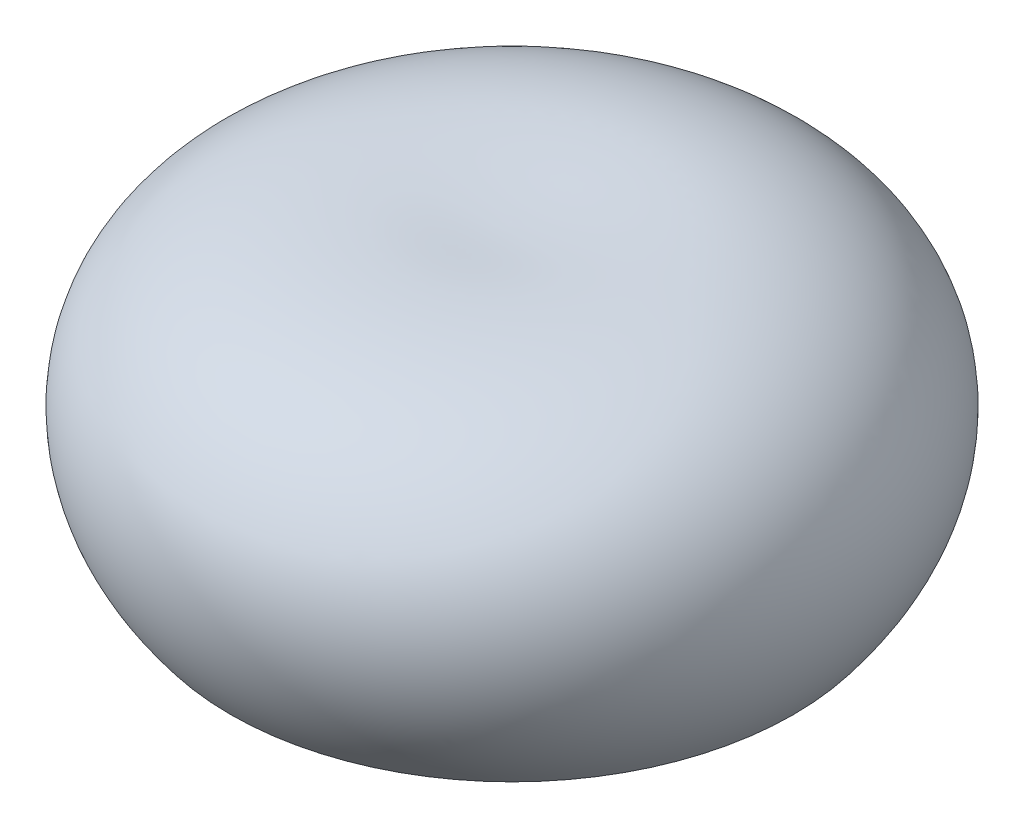
SolidWorks part; units mm, degrees
ref_plane "前视基准面" through (0, 0, 0) normal (0, 0, 1) x (1, 0, 0)
ref_plane "上视基准面" through (0, 0, 0) normal (0, 1, 0) x (1, 0, 0)
ref_plane "右视基准面" through (0, 0, 0) normal (1, 0, 0) x (0, 0, -1)
curve "曲线1"
  spline degree 3 poles (0, 7, 0) (0.0738, 6.9995, 0) (0.1783, 6.9989, 0) (0.3064, 7.0015, 0) (0.3805, 7.0034, 0) (0.4416, 7.0054, 0) (0.4951, 7.0074, 0) (0.5433, 7.0093, 0) (0.5877, 7.0113, 0) (0.629, 7.0132, 0) (0.6679, 7.0151, 0) (0.7047, 7.017, 0) (0.7397, 7.0189, 0) (0.7733, 7.0208, 0) (0.8056, 7.0227, 0) (0.8367, 7.0245, 0) (0.8668, 7.0264, 0) (0.8959, 7.0282, 0) (0.9242, 7.03, 0) (0.9518, 7.0318, 0) (0.9786, 7.0335, 0) (1.0048, 7.0353, 0) (1.0305, 7.037, 0) (1.0555, 7.0387, 0) (1.0801, 7.0405, 0) (1.1041, 7.0421, 0) (1.1278, 7.0438, 0) (1.151, 7.0455, 0) (1.1738, 7.0471, 0) (1.1962, 7.0487, 0) (1.2183, 7.0503, 0) (1.2401, 7.0519, 0) (1.2615, 7.0535, 0) (1.2826, 7.055, 0) (1.3035, 7.0566, 0) (1.3241, 7.0581, 0) (1.3444, 7.0596, 0) (1.3645, 7.0611, 0) (1.3843, 7.0626, 0) (1.4039, 7.064, 0) (1.4233, 7.0654, 0) (1.4425, 7.0669, 0) (1.4614, 7.0683, 0) (1.4802, 7.0697, 0) (1.4988, 7.071, 0) (1.5172, 7.0724, 0) (1.5355, 7.0737, 0) (1.5535, 7.0751, 0) (1.5714, 7.0764, 0) (1.5892, 7.0777, 0) (1.6068, 7.0789, 0) (1.6243, 7.0802, 0) (1.6416, 7.0815, 0) (1.6588, 7.0827, 0) (1.6758, 7.0839, 0) (1.6927, 7.0851, 0) (1.7095, 7.0863, 0) (1.7262, 7.0875, 0) (1.7427, 7.0886, 0) (1.7592, 7.0897, 0) (1.7755, 7.0909, 0) (1.7917, 7.092, 0) (1.8078, 7.0931, 0) (1.8238, 7.0941, 0) (1.8397, 7.0952, 0) (1.8555, 7.0962, 0) (1.8713, 7.0973, 0) (1.8869, 7.0983, 0) (1.9024, 7.0993, 0) (1.9178, 7.1003, 0) (1.9332, 7.1012, 0) (1.9485, 7.1022, 0) (1.9636, 7.1031, 0) (1.9788, 7.104, 0) (1.9938, 7.1049, 0) (2.0087, 7.1058, 0) (2.0236, 7.1067, 0) (2.0384, 7.1076, 0) (2.0531, 7.1084, 0) (2.0678, 7.1092, 0) (2.0823, 7.1101, 0) (2.0969, 7.1109, 0) (2.1113, 7.1116, 0) (2.1257, 7.1124, 0) (2.14, 7.1132, 0) (2.1543, 7.1139, 0) (2.1684, 7.1147, 0) (2.1826, 7.1154, 0) (2.1966, 7.1161, 0) (2.2107, 7.1167, 0) (2.2246, 7.1174, 0) (2.2385, 7.1181, 0) (2.2524, 7.1187, 0) (2.2661, 7.1193, 0) (2.2799, 7.1199, 0) (2.2936, 7.1205, 0) (2.3072, 7.1211, 0) (2.3208, 7.1217, 0) (2.3343, 7.1222, 0) (2.3478, 7.1228, 0) (2.3612, 7.1233, 0) (2.3746, 7.1238, 0) (2.3879, 7.1243, 0) (2.4012, 7.1248, 0) (2.4145, 7.1253, 0) (2.4277, 7.1257, 0) (2.4408, 7.1262, 0) (2.4539, 7.1266, 0) (2.467, 7.127, 0) (2.48, 7.1274, 0) (2.493, 7.1278, 0) (2.506, 7.1281, 0) (2.5189, 7.1285, 0) (2.5317, 7.1288, 0) (2.5446, 7.1292, 0) (2.5574, 7.1295, 0) (2.5701, 7.1298, 0) (2.5828, 7.1301, 0) (2.5955, 7.1303, 0) (2.6081, 7.1306, 0) (2.6207, 7.1308, 0) (2.6333, 7.1311, 0) (2.6458, 7.1313, 0) (2.6583, 7.1315, 0) (2.6708, 7.1317, 0) (2.6832, 7.1318, 0) (2.6956, 7.132, 0) (2.708, 7.1321, 0) (2.7203, 7.1323, 0) (2.7326, 7.1324, 0) (2.7449, 7.1325, 0) (2.7571, 7.1326, 0) (2.7693, 7.1327, 0) (2.7815, 7.1327, 0) (2.7937, 7.1328, 0) (2.8058, 7.1328, 0) (2.8179, 7.1328, 0) (2.8299, 7.1329, 0) (2.8419, 7.1328, 0) (2.8539, 7.1328, 0) (2.8659, 7.1328, 0) (2.8779, 7.1328, 0) (2.8898, 7.1327, 0) (2.9017, 7.1326, 0) (2.9135, 7.1325, 0) (2.9254, 7.1324, 0) (2.9372, 7.1323, 0) (2.949, 7.1322, 0) (2.9607, 7.1321, 0) (2.9725, 7.1319, 0) (2.9842, 7.1317, 0) (2.9958, 7.1316, 0) (3.0075, 7.1314, 0) (3.0191, 7.1312, 0) (3.0307, 7.1309, 0) (3.0423, 7.1307, 0) (3.0539, 7.1305, 0) (3.0654, 7.1302, 0) (3.0769, 7.1299, 0) (3.0884, 7.1296, 0) (3.0999, 7.1293, 0) (3.1114, 7.129, 0) (3.1228, 7.1287, 0) (3.1342, 7.1284, 0) (3.1456, 7.128, 0) (3.1569, 7.1277, 0) (3.1683, 7.1273, 0) (3.1796, 7.1269, 0) (3.1909, 7.1265, 0) (3.2021, 7.1261, 0) (3.2134, 7.1256, 0) (3.2246, 7.1252, 0) (3.2358, 7.1247, 0) (3.247, 7.1243, 0) (3.2582, 7.1238, 0) (3.2694, 7.1233, 0) (3.2805, 7.1228, 0) (3.2916, 7.1222, 0) (3.3027, 7.1217, 0) (3.3138, 7.1211, 0) (3.3248, 7.1206, 0) (3.3359, 7.12, 0) (3.3469, 7.1194, 0) (3.3579, 7.1188, 0) (3.3689, 7.1182, 0) (3.3798, 7.1176, 0) (3.3908, 7.1169, 0) (3.4017, 7.1163, 0) (3.4126, 7.1156, 0) (3.4235, 7.1149, 0) (3.4344, 7.1142, 0) (3.4452, 7.1135, 0) (3.4561, 7.1128, 0) (3.4669, 7.1121, 0) (3.4777, 7.1113, 0) (3.4885, 7.1106, 0) (3.4993, 7.1098, 0) (3.51, 7.109, 0) (3.5208, 7.1082, 0) (3.5315, 7.1074, 0) (3.5422, 7.1066, 0) (3.5529, 7.1058, 0) (3.5635, 7.1049, 0) (3.5742, 7.104, 0) (3.5848, 7.1032, 0) (3.5955, 7.1023, 0) (3.6061, 7.1014, 0) (3.6167, 7.1005, 0) (3.6273, 7.0995, 0) (3.6378, 7.0986, 0) (3.6484, 7.0977, 0) (3.6589, 7.0967, 0) (3.6694, 7.0957, 0) (3.6799, 7.0947, 0) (3.6904, 7.0937, 0) (3.7009, 7.0927, 0) (3.7114, 7.0917, 0) (3.7218, 7.0906, 0) (3.7322, 7.0896, 0) (3.7426, 7.0885, 0) (3.753, 7.0874, 0) (3.7634, 7.0863, 0) (3.7738, 7.0852, 0) (3.7842, 7.0841, 0) (3.7945, 7.083, 0) (3.8049, 7.0818, 0) (3.8152, 7.0807, 0) (3.8255, 7.0795, 0) (3.8358, 7.0783, 0) (3.846, 7.0771, 0) (3.8563, 7.0759, 0) (3.8666, 7.0747, 0) (3.8768, 7.0734, 0) (3.887, 7.0722, 0) (3.8972, 7.0709, 0) (3.9074, 7.0697, 0) (3.9176, 7.0684, 0) (3.9278, 7.0671, 0) (3.938, 7.0658, 0) (3.9481, 7.0644, 0) (3.9582, 7.0631, 0) (3.9684, 7.0618, 0) (3.9785, 7.0604, 0) (3.9886, 7.059, 0) (3.9986, 7.0576, 0) (4.0087, 7.0562, 0) (4.0188, 7.0548, 0) (4.0288, 7.0534, 0) (4.0389, 7.0519, 0) (4.0489, 7.0505, 0) (4.0589, 7.049, 0) (4.0689, 7.0475, 0) (4.0789, 7.0461, 0) (4.0889, 7.0445, 0) (4.0988, 7.043, 0) (4.1088, 7.0415, 0) (4.1187, 7.04, 0) (4.1286, 7.0384, 0) (4.1386, 7.0368, 0) (4.1485, 7.0352, 0) (4.1584, 7.0337, 0) (4.1682, 7.032, 0) (4.1781, 7.0304, 0) (4.188, 7.0288, 0) (4.1978, 7.0271, 0) (4.2076, 7.0255, 0) (4.2175, 7.0238, 0) (4.2273, 7.0221, 0) (4.2371, 7.0204, 0) (4.2469, 7.0187, 0) (4.2567, 7.017, 0) (4.2664, 7.0153, 0) (4.2762, 7.0135, 0) (4.2859, 7.0118, 0) (4.2957, 7.01, 0) (4.3054, 7.0082, 0) (4.3151, 7.0064, 0) (4.3248, 7.0046, 0) (4.3345, 7.0028, 0) (4.3442, 7.0009, 0) (4.3539, 6.9991, 0) (4.3635, 6.9972, 0) (4.3732, 6.9953, 0) (4.3828, 6.9934, 0) (4.3924, 6.9915, 0) (4.4021, 6.9896, 0) (4.4117, 6.9877, 0) (4.4213, 6.9858, 0) (4.4309, 6.9838, 0) (4.4404, 6.9818, 0) (4.45, 6.9799, 0) (4.4596, 6.9779, 0) (4.4691, 6.9759, 0) (4.4786, 6.9738, 0) (4.4882, 6.9718, 0) (4.4977, 6.9698, 0) (4.5072, 6.9677, 0) (4.5167, 6.9656, 0) (4.5262, 6.9635, 0) (4.5356, 6.9615, 0) (4.5451, 6.9593, 0) (4.5546, 6.9572, 0) (4.564, 6.9551, 0) (4.5734, 6.9529, 0) (4.5829, 6.9508, 0) (4.5923, 6.9486, 0) (4.6017, 6.9464, 0) (4.6111, 6.9442, 0) (4.6205, 6.942, 0) (4.6299, 6.9398, 0) (4.6392, 6.9375, 0) (4.6486, 6.9353, 0) (4.6579, 6.933, 0) (4.6673, 6.9307, 0) (4.6766, 6.9284, 0) (4.6859, 6.9261, 0) (4.6952, 6.9238, 0) (4.7045, 6.9215, 0) (4.7138, 6.9192, 0) (4.7231, 6.9168, 0) (4.7324, 6.9144, 0) (4.7416, 6.912, 0) (4.7509, 6.9096, 0) (4.7601, 6.9072, 0) (4.7693, 6.9048, 0) (4.7786, 6.9024, 0) (4.7878, 6.8999, 0) (4.797, 6.8975, 0) (4.8062, 6.895, 0) (4.8154, 6.8925, 0) (4.8245, 6.89, 0) (4.8337, 6.8875, 0) (4.8429, 6.885, 0) (4.852, 6.8824, 0) (4.8612, 6.8799, 0) (4.8703, 6.8773, 0) (4.8794, 6.8747, 0) (4.8885, 6.8721, 0) (4.8976, 6.8695, 0) (4.9067, 6.8669, 0) (4.9158, 6.8643, 0) (4.9249, 6.8616, 0) (4.9339, 6.859, 0) (4.943, 6.8563, 0) (4.952, 6.8536, 0) (4.9611, 6.8509, 0) (4.9701, 6.8482, 0) (4.9791, 6.8455, 0) (4.9881, 6.8428, 0) (4.9971, 6.84, 0) (5.0061, 6.8372, 0) (5.0151, 6.8345, 0) (5.0241, 6.8317, 0) (5.0331, 6.8289, 0) (5.042, 6.8261, 0) (5.051, 6.8232, 0) (5.0599, 6.8204, 0) (5.0688, 6.8175, 0) (5.0778, 6.8147, 0) (5.0867, 6.8118, 0) (5.0956, 6.8089, 0) (5.1045, 6.806, 0) (5.1134, 6.803, 0) (5.1222, 6.8001, 0) (5.1311, 6.7971, 0) (5.14, 6.7942, 0) (5.1488, 6.7912, 0) (5.1576, 6.7882, 0) (5.1665, 6.7852, 0) (5.1753, 6.7822, 0) (5.1841, 6.7792, 0) (5.1929, 6.7761, 0) (5.2017, 6.7731, 0) (5.2105, 6.77, 0) (5.2193, 6.7669, 0) (5.228, 6.7638, 0) (5.2368, 6.7607, 0) (5.2456, 6.7576, 0) (5.2543, 6.7544, 0) (5.263, 6.7513, 0) (5.2718, 6.7481, 0) (5.2805, 6.7449, 0) (5.2892, 6.7417, 0) (5.2979, 6.7385, 0) (5.3066, 6.7353, 0) (5.3153, 6.7321, 0) (5.3239, 6.7288, 0) (5.3326, 6.7256, 0) (5.3412, 6.7223, 0) (5.3499, 6.719, 0) (5.3585, 6.7157, 0) (5.3671, 6.7124, 0) (5.3758, 6.709, 0) (5.3844, 6.7057, 0) (5.393, 6.7023, 0) (5.4016, 6.699, 0) (5.4102, 6.6956, 0) (5.4187, 6.6922, 0) (5.4273, 6.6888, 0) (5.4359, 6.6854, 0) (5.4444, 6.6819, 0) (5.4529, 6.6785, 0) (5.4615, 6.675, 0) (5.47, 6.6715, 0) (5.4785, 6.668, 0) (5.487, 6.6645, 0) (5.4955, 6.661, 0) (5.504, 6.6575, 0) (5.5125, 6.6539, 0) (5.5209, 6.6503, 0) (5.5294, 6.6468, 0) (5.5378, 6.6432, 0) (5.5463, 6.6396, 0) (5.5547, 6.6359, 0) (5.5631, 6.6323, 0) (5.5716, 6.6287, 0) (5.58, 6.625, 0) (5.5884, 6.6213, 0) (5.5968, 6.6176, 0) (5.6051, 6.6139, 0) (5.6135, 6.6102, 0) (5.6219, 6.6065, 0) (5.6302, 6.6027, 0) (5.6386, 6.599, 0) (5.6469, 6.5952, 0) (5.6552, 6.5914, 0) (5.6635, 6.5876, 0) (5.6719, 6.5838, 0) (5.6802, 6.58, 0) (5.6884, 6.5761, 0) (5.6967, 6.5723, 0) (5.705, 6.5684, 0) (5.7133, 6.5645, 0) (5.7215, 6.5606, 0) (5.7298, 6.5567, 0) (5.738, 6.5528, 0) (5.7462, 6.5488, 0) (5.7544, 6.5449, 0) (5.7627, 6.5409, 0) (5.7709, 6.5369, 0) (5.7791, 6.5329, 0) (5.7872, 6.5289, 0) (5.7954, 6.5249, 0) (5.8036, 6.5208, 0) (5.8117, 6.5168, 0) (5.8199, 6.5127, 0) (5.828, 6.5086, 0) (5.8361, 6.5045, 0) (5.8443, 6.5004, 0) (5.8524, 6.4962, 0) (5.8605, 6.4921, 0) (5.8686, 6.4879, 0) (5.8766, 6.4838, 0) (5.8847, 6.4796, 0) (5.8928, 6.4754, 0) (5.9008, 6.4712, 0) (5.9089, 6.4669, 0) (5.9169, 6.4627, 0) (5.9249, 6.4584, 0) (5.933, 6.4541, 0) (5.941, 6.4499, 0) (5.949, 6.4456, 0) (5.957, 6.4412, 0) (5.9649, 6.4369, 0) (5.9729, 6.4326, 0) (5.9809, 6.4282, 0) (5.9888, 6.4238, 0) (5.9968, 6.4194, 0) (6.0047, 6.415, 0) (6.0126, 6.4106, 0) (6.0206, 6.4062, 0) (6.0285, 6.4017, 0) (6.0364, 6.3972, 0) (6.0442, 6.3928, 0) (6.0521, 6.3883, 0) (6.06, 6.3838, 0) (6.0679, 6.3792, 0) (6.0757, 6.3747, 0) (6.0835, 6.3701, 0) (6.0914, 6.3656, 0) (6.0992, 6.361, 0) (6.107, 6.3564, 0) (6.1148, 6.3518, 0) (6.1226, 6.3471, 0) (6.1304, 6.3425, 0) (6.1382, 6.3378, 0) (6.1459, 6.3332, 0) (6.1537, 6.3285, 0) (6.1614, 6.3238, 0) (6.1692, 6.319, 0) (6.1769, 6.3143, 0) (6.1846, 6.3096, 0) (6.1923, 6.3048, 0) (6.2, 6.3, 0) (6.2077, 6.2952, 0) (6.2154, 6.2904, 0) (6.223, 6.2856, 0) (6.2307, 6.2807, 0) (6.2383, 6.2759, 0) (6.246, 6.271, 0) (6.2536, 6.2661, 0) (6.2612, 6.2612, 0) (6.2688, 6.2563, 0) (6.2764, 6.2514, 0) (6.284, 6.2464, 0) (6.2916, 6.2415, 0) (6.2991, 6.2365, 0) (6.3067, 6.2315, 0) (6.3143, 6.2265, 0) (6.3218, 6.2214, 0) (6.3293, 6.2164, 0) (6.3368, 6.2113, 0) (6.3443, 6.2063, 0) (6.3518, 6.2012, 0) (6.3593, 6.1961, 0) (6.3668, 6.191, 0) (6.3743, 6.1858, 0) (6.3817, 6.1807, 0) (6.3892, 6.1755, 0) (6.3966, 6.1703, 0) (6.404, 6.1651, 0) (6.4114, 6.1599, 0) (6.4189, 6.1547, 0) (6.4262, 6.1494, 0) (6.4336, 6.1442, 0) (6.441, 6.1389, 0) (6.4484, 6.1336, 0) (6.4557, 6.1283, 0) (6.4631, 6.123, 0) (6.4704, 6.1177, 0) (6.4777, 6.1123, 0) (6.485, 6.1069, 0) (6.4923, 6.1015, 0) (6.4996, 6.0961, 0) (6.5069, 6.0907, 0) (6.5142, 6.0853, 0) (6.5214, 6.0798, 0) (6.5287, 6.0744, 0) (6.5359, 6.0689, 0) (6.5431, 6.0634, 0) (6.5503, 6.0579, 0) (6.5575, 6.0523, 0) (6.5647, 6.0468, 0) (6.5719, 6.0412, 0) (6.5791, 6.0356, 0) (6.5862, 6.0301, 0) (6.5934, 6.0244, 0) (6.6005, 6.0188, 0) (6.6077, 6.0132, 0) (6.6148, 6.0075, 0) (6.6219, 6.0018, 0) (6.629, 5.9961, 0) (6.6361, 5.9904, 0) (6.6431, 5.9847, 0) (6.6502, 5.979, 0) (6.6572, 5.9732, 0) (6.6643, 5.9674, 0) (6.6713, 5.9616, 0) (6.6783, 5.9558, 0) (6.6853, 5.95, 0) (6.6923, 5.9441, 0) (6.6993, 5.9383, 0) (6.7063, 5.9324, 0) (6.7132, 5.9265, 0) (6.7202, 5.9206, 0) (6.7271, 5.9147, 0) (6.734, 5.9087, 0) (6.7409, 5.9028, 0) (6.7478, 5.8968, 0) (6.7547, 5.8908, 0) (6.7616, 5.8848, 0) (6.7685, 5.8788, 0) (6.7753, 5.8727, 0) (6.7822, 5.8667, 0) (6.789, 5.8606, 0) (6.7958, 5.8545, 0) (6.8026, 5.8484, 0) (6.8094, 5.8423, 0) (6.8162, 5.8361, 0) (6.823, 5.83, 0) (6.8297, 5.8238, 0) (6.8365, 5.8176, 0) (6.8432, 5.8114, 0) (6.8499, 5.8051, 0) (6.8566, 5.7989, 0) (6.8633, 5.7926, 0) (6.87, 5.7863, 0) (6.8767, 5.78, 0) (6.8834, 5.7737, 0) (6.89, 5.7674, 0) (6.8966, 5.761, 0) (6.9033, 5.7547, 0) (6.9099, 5.7483, 0) (6.9165, 5.7419, 0) (6.9231, 5.7355, 0) (6.9296, 5.729, 0) (6.9362, 5.7226, 0) (6.9428, 5.7161, 0) (6.9493, 5.7096, 0) (6.9558, 5.7031, 0) (6.9623, 5.6966, 0) (6.9688, 5.69, 0) (6.9753, 5.6835, 0) (6.9818, 5.6769, 0) (6.9882, 5.6703, 0) (6.9947, 5.6637, 0) (7.0011, 5.657, 0) (7.0075, 5.6504, 0) (7.014, 5.6437, 0) (7.0204, 5.637, 0) (7.0267, 5.6303, 0) (7.0331, 5.6236, 0) (7.0395, 5.6169, 0) (7.0458, 5.6101, 0) (7.0521, 5.6033, 0) (7.0584, 5.5965, 0) (7.0647, 5.5897, 0) (7.071, 5.5829, 0) (7.0773, 5.576, 0) (7.0836, 5.5692, 0) (7.0898, 5.5623, 0) (7.0961, 5.5554, 0) (7.1023, 5.5484, 0) (7.1085, 5.5415, 0) (7.1147, 5.5345, 0) (7.1209, 5.5276, 0) (7.127, 5.5206, 0) (7.1332, 5.5135, 0) (7.1393, 5.5065, 0) (7.1454, 5.4995, 0) (7.1515, 5.4924, 0) (7.1576, 5.4853, 0) (7.1637, 5.4782, 0) (7.1698, 5.4711, 0) (7.1758, 5.4639, 0) (7.1819, 5.4567, 0) (7.1879, 5.4496, 0) (7.1939, 5.4424, 0) (7.1999, 5.4351, 0) (7.2059, 5.4279, 0) (7.2119, 5.4206, 0) (7.2178, 5.4134, 0) (7.2238, 5.4061, 0) (7.2297, 5.3987, 0) (7.2356, 5.3914, 0) (7.2415, 5.3841, 0) (7.2474, 5.3767, 0) (7.2532, 5.3693, 0) (7.2591, 5.3619, 0) (7.2649, 5.3544, 0) (7.2707, 5.347, 0) (7.2765, 5.3395, 0) (7.2823, 5.332, 0) (7.2881, 5.3245, 0) (7.2939, 5.317, 0) (7.2996, 5.3094, 0) (7.3053, 5.3019, 0) (7.311, 5.2943, 0) (7.3167, 5.2867, 0) (7.3224, 5.279, 0) (7.3281, 5.2714, 0) (7.3337, 5.2637, 0) (7.3394, 5.256, 0) (7.345, 5.2483, 0) (7.3506, 5.2406, 0) (7.3562, 5.2329, 0) (7.3618, 5.2251, 0) (7.3673, 5.2173, 0) (7.3729, 5.2095, 0) (7.3784, 5.2017, 0) (7.3839, 5.1938, 0) (7.3894, 5.1859, 0) (7.3949, 5.1781, 0) (7.4003, 5.1702, 0) (7.4058, 5.1622, 0) (7.4112, 5.1543, 0) (7.4166, 5.1463, 0) (7.422, 5.1383, 0) (7.4274, 5.1303, 0) (7.4327, 5.1223, 0) (7.4381, 5.1142, 0) (7.4434, 5.1061, 0) (7.4487, 5.098, 0) (7.454, 5.0899, 0) (7.4593, 5.0818, 0) (7.4646, 5.0736, 0) (7.4698, 5.0655, 0) (7.475, 5.0573, 0) (7.4802, 5.049, 0) (7.4854, 5.0408, 0) (7.4906, 5.0325, 0) (7.4958, 5.0243, 0) (7.5009, 5.016, 0) (7.506, 5.0076, 0) (7.5111, 4.9993, 0) (7.5162, 4.9909, 0) (7.5213, 4.9825, 0) (7.5263, 4.9741, 0) (7.5314, 4.9657, 0) (7.5364, 4.9572, 0) (7.5414, 4.9487, 0) (7.5464, 4.9402, 0) (7.5513, 4.9317, 0) (7.5563, 4.9232, 0) (7.5612, 4.9146, 0) (7.5661, 4.906, 0) (7.571, 4.8974, 0) (7.5758, 4.8888, 0) (7.5807, 4.8801, 0) (7.5855, 4.8715, 0) (7.5903, 4.8628, 0) (7.5951, 4.8541, 0) (7.5999, 4.8453, 0) (7.6047, 4.8366, 0) (7.6094, 4.8278, 0) (7.6141, 4.819, 0) (7.6188, 4.8101, 0) (7.6235, 4.8013, 0) (7.6282, 4.7924, 0) (7.6328, 4.7835, 0) (7.6374, 4.7746, 0) (7.642, 4.7656, 0) (7.6466, 4.7567, 0) (7.6512, 4.7477, 0) (7.6557, 4.7387, 0) (7.6602, 4.7296, 0) (7.6647, 4.7206, 0) (7.6692, 4.7115, 0) (7.6737, 4.7024, 0) (7.6781, 4.6932, 0) (7.6825, 4.6841, 0) (7.6869, 4.6749, 0) (7.6913, 4.6657, 0) (7.6957, 4.6565, 0) (7.7, 4.6472, 0) (7.7043, 4.638, 0) (7.7086, 4.6287, 0) (7.7129, 4.6193, 0) (7.7172, 4.61, 0) (7.7214, 4.6006, 0) (7.7256, 4.5912, 0) (7.7298, 4.5818, 0) (7.734, 4.5724, 0) (7.7381, 4.5629, 0) (7.7422, 4.5534, 0) (7.7463, 4.5439, 0) (7.7504, 4.5344, 0) (7.7545, 4.5248, 0) (7.7585, 4.5152, 0) (7.7625, 4.5056, 0) (7.7665, 4.496, 0) (7.7705, 4.4863, 0) (7.7744, 4.4766, 0) (7.7784, 4.4669, 0) (7.7823, 4.4571, 0) (7.7861, 4.4474, 0) (7.79, 4.4376, 0) (7.7938, 4.4278, 0) (7.7976, 4.4179, 0) (7.8014, 4.4081, 0) (7.8052, 4.3982, 0) (7.8089, 4.3882, 0) (7.8127, 4.3783, 0) (7.8164, 4.3683, 0) (7.82, 4.3583, 0) (7.8237, 4.3483, 0) (7.8273, 4.3382, 0) (7.8309, 4.3282, 0) (7.8345, 4.3181, 0) (7.838, 4.3079, 0) (7.8415, 4.2978, 0) (7.845, 4.2876, 0) (7.8485, 4.2774, 0) (7.852, 4.2671, 0) (7.8554, 4.2569, 0) (7.8588, 4.2466, 0) (7.8622, 4.2362, 0) (7.8655, 4.2259, 0) (7.8688, 4.2155, 0) (7.8721, 4.2051, 0) (7.8754, 4.1947, 0) (7.8786, 4.1842, 0) (7.8819, 4.1737, 0) (7.8851, 4.1632, 0) (7.8882, 4.1527, 0) (7.8914, 4.1421, 0) (7.8945, 4.1315, 0) (7.8976, 4.1209, 0) (7.9006, 4.1102, 0) (7.9037, 4.0995, 0) (7.9067, 4.0888, 0) (7.9096, 4.078, 0) (7.9126, 4.0673, 0) (7.9155, 4.0565, 0) (7.9184, 4.0456, 0) (7.9213, 4.0348, 0) (7.9241, 4.0239, 0) (7.9269, 4.0129, 0) (7.9297, 4.002, 0) (7.9325, 3.991, 0) (7.9352, 3.98, 0) (7.9379, 3.9689, 0) (7.9406, 3.9579, 0) (7.9432, 3.9468, 0) (7.9458, 3.9356, 0) (7.9484, 3.9244, 0) (7.951, 3.9132, 0) (7.9535, 3.902, 0) (7.956, 3.8908, 0) (7.9584, 3.8795, 0) (7.9609, 3.8681, 0) (7.9633, 3.8568, 0) (7.9656, 3.8454, 0) (7.968, 3.834, 0) (7.9703, 3.8225, 0) (7.9725, 3.811, 0) (7.9748, 3.7995, 0) (7.977, 3.7879, 0) (7.9792, 3.7763, 0) (7.9813, 3.7647, 0) (7.9834, 3.7531, 0) (7.9855, 3.7414, 0) (7.9876, 3.7297, 0) (7.9896, 3.7179, 0) (7.9916, 3.7061, 0) (7.9935, 3.6943, 0) (7.9955, 3.6824, 0) (7.9973, 3.6705, 0) (7.9992, 3.6586, 0) (8.001, 3.6466, 0) (8.0028, 3.6346, 0) (8.0045, 3.6226, 0) (8.0062, 3.6105, 0) (8.0079, 3.5984, 0) (8.0096, 3.5863, 0) (8.0112, 3.5741, 0) (8.0127, 3.5619, 0) (8.0143, 3.5496, 0) (8.0158, 3.5373, 0) (8.0172, 3.525, 0) (8.0187, 3.5126, 0) (8.0201, 3.5002, 0) (8.0214, 3.4878, 0) (8.0227, 3.4753, 0) (8.024, 3.4628, 0) (8.0252, 3.4502, 0) (8.0264, 3.4376, 0) (8.0276, 3.425, 0) (8.0287, 3.4123, 0) (8.0298, 3.3996, 0) (8.0308, 3.3868, 0) (8.0318, 3.374, 0) (8.0328, 3.3612, 0) (8.0337, 3.3483, 0) (8.0346, 3.3354, 0) (8.0354, 3.3224, 0) (8.0362, 3.3094, 0) (8.037, 3.2964, 0) (8.0377, 3.2833, 0) (8.0384, 3.2701, 0) (8.039, 3.257, 0) (8.0396, 3.2437, 0) (8.0401, 3.2305, 0) (8.0406, 3.2172, 0) (8.0411, 3.2038, 0) (8.0415, 3.1904, 0) (8.0419, 3.177, 0) (8.0422, 3.1635, 0) (8.0425, 3.1499, 0) (8.0427, 3.1364, 0) (8.0429, 3.1227, 0) (8.043, 3.109, 0) (8.0431, 3.0953, 0) (8.0431, 3.0815, 0) (8.0431, 3.0677, 0) (8.0431, 3.0539, 0) (8.043, 3.0399, 0) (8.0428, 3.026, 0) (8.0426, 3.0119, 0) (8.0423, 2.9979, 0) (8.042, 2.9837, 0) (8.0417, 2.9696, 0) (8.0413, 2.9553, 0) (8.0408, 2.9411, 0) (8.0403, 2.9267, 0) (8.0397, 2.9123, 0) (8.0391, 2.8979, 0) (8.0384, 2.8834, 0) (8.0377, 2.8688, 0) (8.0369, 2.8542, 0) (8.0361, 2.8396, 0) (8.0352, 2.8248, 0) (8.0342, 2.8101, 0) (8.0332, 2.7952, 0) (8.0321, 2.7803, 0) (8.031, 2.7653, 0) (8.0298, 2.7503, 0) (8.0286, 2.7352, 0) (8.0272, 2.7201, 0) (8.0259, 2.7049, 0) (8.0244, 2.6896, 0) (8.0229, 2.6743, 0) (8.0214, 2.6589, 0) (8.0197, 2.6434, 0) (8.018, 2.6279, 0) (8.0163, 2.6123, 0) (8.0144, 2.5966, 0) (8.0125, 2.5809, 0) (8.0106, 2.5651, 0) (8.0085, 2.5492, 0) (8.0064, 2.5332, 0) (8.0042, 2.5172, 0) (8.002, 2.5011, 0) (7.9997, 2.4849, 0) (7.9973, 2.4687, 0) (7.9948, 2.4523, 0) (7.9922, 2.4359, 0) (7.9896, 2.4194, 0) (7.9869, 2.4028, 0) (7.9841, 2.3862, 0) (7.9812, 2.3694, 0) (7.9783, 2.3526, 0) (7.9752, 2.3357, 0) (7.9721, 2.3187, 0) (7.9689, 2.3016, 0) (7.9656, 2.2844, 0) (7.9622, 2.2672, 0) (7.9587, 2.2498, 0) (7.9552, 2.2324, 0) (7.9515, 2.2148, 0) (7.9477, 2.1971, 0) (7.9439, 2.1794, 0) (7.9399, 2.1615, 0) (7.9359, 2.1435, 0) (7.9317, 2.1255, 0) (7.9274, 2.1073, 0) (7.9231, 2.089, 0) (7.9186, 2.0706, 0) (7.914, 2.052, 0) (7.9093, 2.0334, 0) (7.9045, 2.0146, 0) (7.8995, 1.9957, 0) (7.8945, 1.9767, 0) (7.8893, 1.9576, 0) (7.884, 1.9383, 0) (7.8786, 1.9189, 0) (7.873, 1.8993, 0) (7.8673, 1.8796, 0) (7.8615, 1.8597, 0) (7.8555, 1.8397, 0) (7.8494, 1.8196, 0) (7.8431, 1.7993, 0) (7.8367, 1.7788, 0) (7.8301, 1.7581, 0) (7.8234, 1.7373, 0) (7.8165, 1.7163, 0) (7.8094, 1.6951, 0) (7.8022, 1.6738, 0) (7.7948, 1.6522, 0) (7.7872, 1.6304, 0) (7.7794, 1.6084, 0) (7.7714, 1.5862, 0) (7.7632, 1.5638, 0) (7.7548, 1.5411, 0) (7.7461, 1.5182, 0) (7.7373, 1.4951, 0) (7.7282, 1.4717, 0) (7.7188, 1.448, 0) (7.7093, 1.424, 0) (7.6994, 1.3998, 0) (7.6893, 1.3752, 0) (7.6789, 1.3503, 0) (7.6681, 1.3251, 0) (7.6571, 1.2995, 0) (7.6457, 1.2735, 0) (7.634, 1.2471, 0) (7.6219, 1.2203, 0) (7.6095, 1.1931, 0) (7.5966, 1.1654, 0) (7.5833, 1.1372, 0) (7.5695, 1.1084, 0) (7.5552, 1.0791, 0) (7.5404, 1.0491, 0) (7.525, 1.0185, 0) (7.5091, 0.9872, 0) (7.4924, 0.9551, 0) (7.475, 0.9221, 0) (7.4568, 0.8881, 0) (7.4377, 0.8532, 0) (7.4177, 0.817, 0) (7.3965, 0.7795, 0) (7.374, 0.7405, 0) (7.3502, 0.6997, 0) (7.3246, 0.6569, 0) (7.297, 0.6116, 0) (7.2669, 0.5632, 0) (7.2337, 0.511, 0) (7.1963, 0.4536, 0) (7.1528, 0.3886, 0) (7.0992, 0.3106, 0) (7.0057, 0.179, 0) (6.9269, 0.0739, 0) (6.8715, 0, 0) knots 0 0 0 0 0.016298 0.023067 0.028274 0.032675 0.036563 0.040086 0.043333 0.046364 0.049217 0.051922 0.054501 0.056971 0.059346 0.061636 0.063851 0.065998 0.068084 0.070114 0.072093 0.074025 0.075913 0.077761 0.079571 0.081346 0.083088 0.0848 0.086482 0.088137 0.089766 0.091371 0.092952 0.094511 0.096049 0.097567 0.099066 0.100547 0.10201 0.103456 0.104887 0.106302 0.107702 0.109087 0.110459 0.111818 0.113164 0.114497 0.115819 0.117129 0.118427 0.119715 0.120993 0.12226 0.123518 0.124766 0.126004 0.127234 0.128455 0.129667 0.130871 0.132067 0.133256 0.134436 0.135609 0.136775 0.137933 0.139085 0.14023 0.141368 0.1425 0.143626 0.144745 0.145859 0.146966 0.148068 0.149164 0.150255 0.15134 0.15242 0.153495 0.154564 0.155629 0.156689 0.157744 0.158794 0.159839 0.160881 0.161917 0.16295 0.163978 0.165001 0.166021 0.167037 0.168049 0.169056 0.17006 0.17106 0.172057 0.173049 0.174039 0.175024 0.176006 0.176985 0.17796 0.178932 0.179901 0.180866 0.181829 0.182788 0.183744 0.184697 0.185647 0.186594 0.187538 0.18848 0.189418 0.190354 0.191287 0.192217 0.193145 0.19407 0.194992 0.195912 0.19683 0.197744 0.198657 0.199567 0.200474 0.201379 0.202282 0.203183 0.204081 0.204977 0.205871 0.206762 0.207652 0.208539 0.209424 0.210307 0.211188 0.212067 0.212944 0.213819 0.214692 0.215563 0.216432 0.2173 0.218165 0.219028 0.21989 0.22075 0.221608 0.222464 0.223318 0.224171 0.225022 0.225872 0.226719 0.227565 0.228409 0.229252 0.230093 0.230933 0.23177 0.232607 0.233442 0.234275 0.235106 0.235937 0.236765 0.237593 0.238418 0.239243 0.240066 0.240887 0.241707 0.242526 0.243343 0.244159 0.244974 0.245787 0.246599 0.24741 0.248219 0.249027 0.249834 0.25064 0.251444 0.252247 0.253049 0.253849 0.254649 0.255447 0.256244 0.25704 0.257834 0.258628 0.25942 0.260212 0.261002 0.261791 0.262579 0.263366 0.264151 0.264936 0.26572 0.266502 0.267284 0.268064 0.268844 0.269622 0.2704 0.271176 0.271951 0.272726 0.273499 0.274272 0.275043 0.275814 0.276583 0.277352 0.27812 0.278887 0.279653 0.280418 0.281182 0.281945 0.282707 0.283469 0.284229 0.284989 0.285748 0.286506 0.287263 0.28802 0.288775 0.28953 0.290284 0.291037 0.291789 0.29254 0.293291 0.294041 0.29479 0.295538 0.296286 0.297033 0.297779 0.298524 0.299269 0.300012 0.300756 0.301498 0.302239 0.30298 0.303721 0.30446 0.305199 0.305937 0.306674 0.307411 0.308147 0.308882 0.309617 0.310351 0.311085 0.311817 0.312549 0.313281 0.314012 0.314742 0.315471 0.3162 0.316928 0.317656 0.318383 0.31911 0.319835 0.320561 0.321285 0.322009 0.322733 0.323456 0.324178 0.3249 0.325621 0.326341 0.327062 0.327781 0.3285 0.329218 0.329936 0.330653 0.33137 0.332086 0.332802 0.333517 0.334232 0.334946 0.33566 0.336373 0.337086 0.337798 0.338509 0.339221 0.339931 0.340641 0.341351 0.34206 0.342769 0.343477 0.344185 0.344892 0.345599 0.346305 0.347011 0.347717 0.348422 0.349126 0.349831 0.350534 0.351238 0.35194 0.352643 0.353345 0.354046 0.354748 0.355448 0.356149 0.356849 0.357548 0.358247 0.358946 0.359644 0.360342 0.361039 0.361737 0.362433 0.36313 0.363826 0.364521 0.365216 0.365911 0.366606 0.3673 0.367994 0.368687 0.36938 0.370073 0.370765 0.371457 0.372149 0.37284 0.373531 0.374222 0.374912 0.375602 0.376291 0.376981 0.37767 0.378358 0.379047 0.379735 0.380422 0.38111 0.381797 0.382483 0.38317 0.383856 0.384542 0.385228 0.385913 0.386598 0.387283 0.387967 0.388651 0.389335 0.390018 0.390702 0.391385 0.392068 0.39275 0.393432 0.394114 0.394796 0.395477 0.396159 0.396839 0.39752 0.3982 0.398881 0.399561 0.40024 0.40092 0.401599 0.402278 0.402957 0.403635 0.404314 0.404992 0.405669 0.406347 0.407024 0.407702 0.408379 0.409055 0.409732 0.410408 0.411084 0.41176 0.412436 0.413112 0.413787 0.414462 0.415137 0.415812 0.416486 0.417161 0.417835 0.418509 0.419183 0.419856 0.42053 0.421203 0.421876 0.422549 0.423222 0.423895 0.424567 0.42524 0.425912 0.426584 0.427256 0.427928 0.428599 0.429271 0.429942 0.430613 0.431284 0.431955 0.432626 0.433296 0.433967 0.434637 0.435307 0.435977 0.436647 0.437317 0.437987 0.438657 0.439326 0.439996 0.440665 0.441334 0.442003 0.442672 0.443341 0.44401 0.444678 0.445347 0.446015 0.446684 0.447352 0.44802 0.448689 0.449357 0.450025 0.450693 0.45136 0.452028 0.452696 0.453363 0.454031 0.454698 0.455366 0.456033 0.456701 0.457368 0.458035 0.458702 0.459369 0.460036 0.460703 0.46137 0.462037 0.462704 0.463371 0.464038 0.464705 0.465372 0.466038 0.466705 0.467372 0.468038 0.468705 0.469372 0.470038 0.470705 0.471372 0.472038 0.472705 0.473371 0.474038 0.474705 0.475371 0.476038 0.476704 0.477371 0.478038 0.478704 0.479371 0.480038 0.480704 0.481371 0.482038 0.482705 0.483372 0.484038 0.484705 0.485372 0.486039 0.486706 0.487373 0.488041 0.488708 0.489375 0.490042 0.49071 0.491377 0.492044 0.492712 0.49338 0.494047 0.494715 0.495383 0.496051 0.496719 0.497387 0.498055 0.498723 0.499392 0.50006 0.500728 0.501397 0.502066 0.502735 0.503404 0.504073 0.504742 0.505411 0.50608 0.50675 0.507419 0.508089 0.508759 0.509429 0.510099 0.510769 0.51144 0.51211 0.512781 0.513452 0.514123 0.514794 0.515465 0.516136 0.516808 0.51748 0.518152 0.518824 0.519496 0.520168 0.520841 0.521514 0.522187 0.52286 0.523533 0.524207 0.52488 0.525554 0.526228 0.526903 0.527577 0.528252 0.528927 0.529602 0.530277 0.530953 0.531629 0.532305 0.532981 0.533657 0.534334 0.535011 0.535688 0.536366 0.537043 0.537721 0.538399 0.539078 0.539756 0.540435 0.541115 0.541794 0.542474 0.543154 0.543834 0.544515 0.545196 0.545877 0.546558 0.54724 0.547922 0.548605 0.549287 0.54997 0.550654 0.551337 0.552021 0.552706 0.55339 0.554075 0.55476 0.555446 0.556132 0.556818 0.557505 0.558192 0.558879 0.559567 0.560255 0.560944 0.561632 0.562322 0.563011 0.563701 0.564392 0.565082 0.565774 0.566465 0.567157 0.567849 0.568542 0.569235 0.569929 0.570623 0.571318 0.572012 0.572708 0.573404 0.5741 0.574797 0.575494 0.576191 0.576889 0.577588 0.578287 0.578987 0.579687 0.580387 0.581088 0.581789 0.582491 0.583194 0.583897 0.5846 0.585304 0.586009 0.586714 0.58742 0.588126 0.588832 0.58954 0.590247 0.590956 0.591665 0.592374 0.593084 0.593795 0.594506 0.595218 0.59593 0.596643 0.597357 0.598071 0.598786 0.599501 0.600218 0.600934 0.601652 0.60237 0.603088 0.603808 0.604528 0.605248 0.60597 0.606692 0.607414 0.608138 0.608862 0.609587 0.610312 0.611038 0.611765 0.612493 0.613221 0.61395 0.61468 0.615411 0.616142 0.616875 0.617607 0.618341 0.619076 0.619811 0.620547 0.621284 0.622022 0.62276 0.6235 0.62424 0.624981 0.625723 0.626466 0.627209 0.627954 0.628699 0.629445 0.630193 0.630941 0.63169 0.63244 0.63319 0.633942 0.634695 0.635449 0.636203 0.636959 0.637715 0.638473 0.639231 0.639991 0.640751 0.641513 0.642275 0.643039 0.643804 0.644569 0.645336 0.646104 0.646873 0.647643 0.648414 0.649186 0.649959 0.650734 0.651509 0.652286 0.653064 0.653843 0.654623 0.655405 0.656187 0.656971 0.657756 0.658542 0.65933 0.660119 0.660909 0.6617 0.662493 0.663286 0.664081 0.664878 0.665676 0.666475 0.667275 0.668077 0.66888 0.669685 0.670491 0.671298 0.672107 0.672917 0.673729 0.674542 0.675357 0.676173 0.676991 0.67781 0.678631 0.679453 0.680277 0.681102 0.681929 0.682757 0.683588 0.684419 0.685253 0.686088 0.686925 0.687763 0.688603 0.689445 0.690289 0.691134 0.691981 0.69283 0.693681 0.694533 0.695388 0.696244 0.697102 0.697962 0.698824 0.699688 0.700553 0.701421 0.702291 0.703162 0.704036 0.704912 0.70579 0.70667 0.707551 0.708436 0.709322 0.71021 0.711101 0.711994 0.712889 0.713786 0.714685 0.715587 0.716491 0.717398 0.718307 0.719218 0.720132 0.721048 0.721966 0.722887 0.723811 0.724737 0.725666 0.726597 0.727531 0.728467 0.729407 0.730349 0.731293 0.732241 0.733191 0.734144 0.7351 0.736059 0.737021 0.737986 0.738954 0.739924 0.740898 0.741875 0.742855 0.743839 0.744825 0.745815 0.746808 0.747804 0.748804 0.749807 0.750814 0.751824 0.752837 0.753854 0.754875 0.7559 0.756928 0.75796 0.758996 0.760035 0.761079 0.762126 0.763178 0.764233 0.765293 0.766357 0.767425 0.768497 0.769574 0.770655 0.77174 0.772831 0.773925 0.775025 0.776129 0.777238 0.778351 0.77947 0.780594 0.781722 0.782856 0.783996 0.78514 0.78629 0.787446 0.788607 0.789773 0.790946 0.792124 0.793308 0.794499 0.795695 0.796898 0.798107 0.799322 0.800545 0.801773 0.803009 0.804252 0.805501 0.806758 0.808023 0.809295 0.810574 0.811861 0.813156 0.81446 0.815771 0.817091 0.81842 0.819757 0.821103 0.822459 0.823824 0.825198 0.826582 0.827977 0.829381 0.830796 0.832222 0.833659 0.835107 0.836567 0.838039 0.839522 0.841019 0.842528 0.84405 0.845586 0.847136 0.848701 0.85028 0.851874 0.853485 0.855111 0.856754 0.858415 0.860093 0.861791 0.863507 0.865243 0.867 0.868778 0.870578 0.872402 0.87425 0.876123 0.878022 0.879949 0.881905 0.88389 0.885908 0.887958 0.890044 0.892167 0.894329 0.896532 0.89878 0.901075 0.903419 0.905818 0.908275 0.910794 0.913381 0.916041 0.918782 0.921613 0.924542 0.927581 0.930744 0.934048 0.937516 0.941175 0.945061 0.949227 0.953744 0.958724 0.964357 0.971007 0.979618 1 1 1 1
sketch "草图3" plane through (0, 0, 0) normal (0, 0, 1) x (1, 0, 0)
  line L0 (0, 7) -> (0, 0)
  line L1 (6.8715, 0) -> (0, 0)
  spline S0 degree 3 number of poles 1003 (0, 7) -> (6.8715, 0) construction
  spline S1 degree 3 number of poles 1003 (0, 7) -> (6.8715, 0)
revolve "旋转1" add sketch "草图3" angle 360 about L0
sketch "草图4" plane through (0, 0, 0) normal (0, -1, 0) x (-1, 0, 0)
  line L0 (0, -5) -> (0, 5)
  arc A0 (0, -5) -> (0, 5) centre (0, 0) cw
revolve "切除-旋转1" cut sketch "草图4" angle 360 about L0
